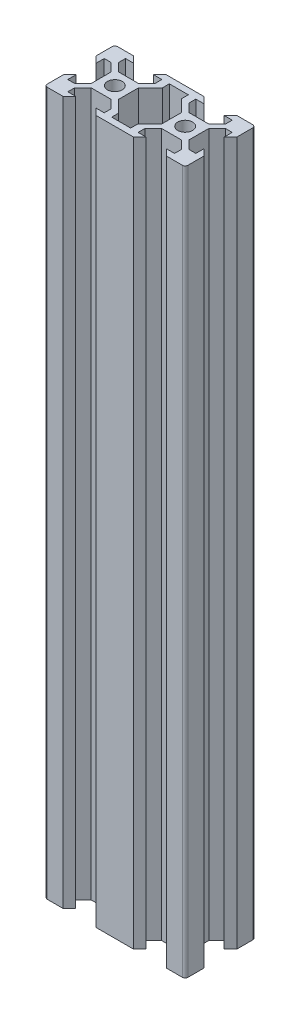
SolidWorks part; units mm, degrees
ref_plane "Front Plane" through (0, 0, 0) normal (0, 0, 1) x (1, 0, 0)
ref_plane "Top Plane" through (0, 0, 0) normal (0, 1, 0) x (1, 0, 0)
ref_plane "Right Plane" through (0, 0, 0) normal (1, 0, 0) x (0, 0, -1)
sketch "Sketch3" plane through (0, 0, 0) normal (0, 1, 0) x (1, 0, 0)
  line L0 (-19.2, -10) -> (-14.7286, -10)
  line L1 (-20, -9.2) -> (-20, -4.6193)
  line L2 (-19.2, 10) -> (-14.6523, 10)
  line L5 (-20, 4.6956) -> (-18.2, 2.8956)
  line L6 (-14.7286, -10) -> (-12.9286, -8.2)
  line L7 (-20, -4.6193) -> (-18.2, -2.8193)
  line L8 (-20, 10) -> (-20, 0) construction
  line L9 (-15.1793, 8.2) -> (-12.8523, 8.2)
  line L10 (-18.2, -5.1793) -> (-18.2, -2.8193)
  line L19 (-4.8207, 6.24) -> (-7.16, 3.9007)
  line L20 (-15.1793, -6.24) -> (-12.84, -3.9007)
  line L21 (-16.24, 5.1793) -> (-13.9007, 2.84)
  line L22 (-2.6993, -6.24) -> (-6.0993, -2.84)
  line L23 (-20, 0) -> (-20, -4.6193) construction
  line L24 (20, 10) -> (20, 0) construction
  line L26 (20, 0) -> (-20, 0) construction
  line L27 (-15.1793, -8.2) -> (-12.9286, -8.2)
  line L28 (10, 3.9007) -> (10, -3.9007) construction
  line L29 (-15.1793, 6.24) -> (-15.1793, 8.2)
  line L30 (-16.24, 5.1793) -> (-18.2, 5.1793)
  line L31 (-4.8207, 6.24) -> (-4.8207, 8.2)
  line L32 (15.1793, 8.2) -> (12.8523, 8.2)
  line L33 (13.9007, -2.84) -> (16.24, -5.1793)
  line L34 (-4.8207, -6.24) -> (-4.8207, -8.2)
  line L35 (-15.1793, -6.24) -> (-15.1793, -8.2)
  line L36 (-13.9007, -2.84) -> (-13.9007, 2.84)
  line L37 (-16.24, -5.1793) -> (-18.2, -5.1793)
  line L42 (-6.0993, -2.84) -> (-6.0993, 2.84)
  line L43 (-12.84, 3.9007) -> (-7.16, 3.9007)
  line L44 (-12.84, -3.9007) -> (-7.16, -3.9007)
  line L45 (0, 10) -> (0, -10) construction
  line L48 (7.16, -3.9007) -> (4.8207, -6.24)
  line L49 (20, -4.6193) -> (20, 0) construction
  line L50 (-10, -3.9007) -> (-10, 3.9007) construction
  line L56 (5.3044, -10) -> (0, -10)
  line L61 (6.0993, 2.84) -> (2.6993, 6.24)
  line L62 (12.84, -3.9007) -> (7.16, -3.9007)
  line L63 (12.84, 3.9007) -> (7.16, 3.9007)
  line L64 (6.0993, -2.84) -> (6.0993, 2.84)
  line L65 (16.24, -5.1793) -> (18.2, -5.1793)
  line L66 (13.9007, -2.84) -> (13.9007, 2.84)
  line L67 (15.1793, -6.24) -> (15.1793, -8.2)
  line L68 (4.8207, -6.24) -> (4.8207, -8.2)
  line L71 (4.8207, 6.24) -> (4.8207, 8.2)
  line L72 (16.24, 5.1793) -> (18.2, 5.1793)
  line L73 (15.1793, 6.24) -> (15.1793, 8.2)
  line L74 (2.6993, -6.24) -> (6.0993, -2.84)
  line L75 (16.24, 5.1793) -> (13.9007, 2.84)
  line L76 (15.1793, -6.24) -> (12.84, -3.9007)
  line L77 (4.8207, 6.24) -> (7.16, 3.9007)
  line L86 (20, -4.6193) -> (18.2, -2.8193)
  line L87 (14.7286, -10) -> (12.9286, -8.2)
  line L88 (20, 4.6956) -> (18.2, 2.8956)
  line L90 (19.2, 10) -> (14.6523, 10)
  line L91 (20, -9.2) -> (20, -4.6193)
  line L92 (19.2, -10) -> (14.7286, -10)
  line L93 (20, 4.6956) -> (20, 9.2)
  line L94 (18.2, 2.8956) -> (18.2, 5.1793)
  line L95 (15.1793, -8.2) -> (12.9286, -8.2)
  line L96 (-2.6993, -8.2) -> (2.6993, -8.2)
  line L98 (2.6993, -8.2) -> (2.6993, -6.24)
  line L99 (-2.6993, -8.2) -> (-2.6993, -6.24)
  line L101 (7.1044, -8.2) -> (4.8207, -8.2)
  line L102 (18.2, -5.1793) -> (18.2, -2.8193)
  line L103 (-5.3044, -10) -> (0, -10)
  line L105 (2.6993, 8.2) -> (-2.6993, 8.2)
  line L107 (7.1044, -8.2) -> (5.3044, -10)
  line L108 (-7.1044, -8.2) -> (-4.8207, -8.2)
  line L110 (-7.1044, -8.2) -> (-5.3044, -10)
  line L111 (-2.6993, 8.2) -> (-2.6993, 6.24)
  line L112 (2.6993, 8.2) -> (2.6993, 6.24)
  line L114 (-20, 4.6956) -> (-20, 9.2)
  line L116 (-18.2, 2.8956) -> (-18.2, 5.1793)
  line L118 (-12.8523, 8.2) -> (-14.6523, 10)
  line L119 (-7.16, -3.9007) -> (-4.8207, -6.24)
  line L123 (-6.0993, 2.84) -> (-2.6993, 6.24)
  line L124 (-7.1807, 8.2) -> (-5.3807, 10)
  line L127 (-7.1807, 8.2) -> (-4.8207, 8.2)
  line L129 (-5.3807, 10) -> (0, 10)
  line L131 (5.3807, 10) -> (0, 10)
  line L132 (7.1807, 8.2) -> (4.8207, 8.2)
  line L133 (7.1807, 8.2) -> (5.3807, 10)
  line L135 (12.8523, 8.2) -> (14.6523, 10)
  line L136 (12.84, 3.9007) -> (15.1793, 6.24)
  line L137 (-12.84, 3.9007) -> (-15.1793, 6.24)
  line L141 (-13.9007, -2.84) -> (-16.24, -5.1793)
  circle A0 centre (-10, 0) radius 2.1
  arc A2 (-19.2, 10) -> (-20, 9.2) centre (-19.2, 9.2) ccw
  arc A3 (-20, -9.2) -> (-19.2, -10) centre (-19.2, -9.2) ccw
  arc A4 (19.2, -10) -> (20, -9.2) centre (19.2, -9.2) ccw
  arc A5 (19.2, 10) -> (20, 9.2) centre (19.2, 9.2) cw
  circle A18 centre (10, 0) radius 2.1
  point P17 (-20, -10)
  point P133 (-20, 10)
  point P134 (20, -10)
  point P136 (20, 10)
  dimension "D3" = 20
  dimension "D2" = 0.8
  dimension "D1" = 40
extrude "Saliente-Extruir1" add sketch "Sketch3" along normal blind 200
